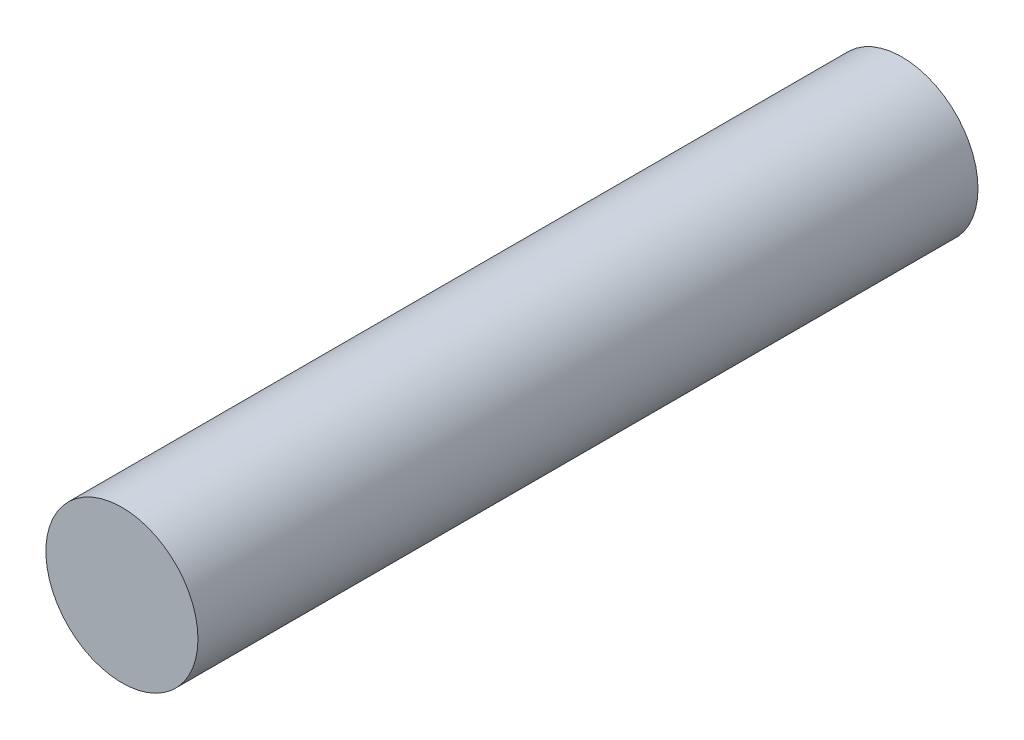
SolidWorks part; units mm, degrees
ref_plane "Front Plane" through (0, 0, 0) normal (0, 0, 1) x (1, 0, 0)
ref_plane "Top Plane" through (0, 0, 0) normal (0, 1, 0) x (1, 0, 0)
ref_plane "Right Plane" through (0, 0, 0) normal (1, 0, 0) x (0, 0, -1)
sketch "Sketch1" plane through (0, 0, 0) normal (0, 0, 1) x (1, 0, 0)
  circle A0 centre (0, 0) radius 1.95
  dimension "D1" = 3.9
extrude "Boss-Extrude1" add sketch "Sketch1" along normal blind 20
